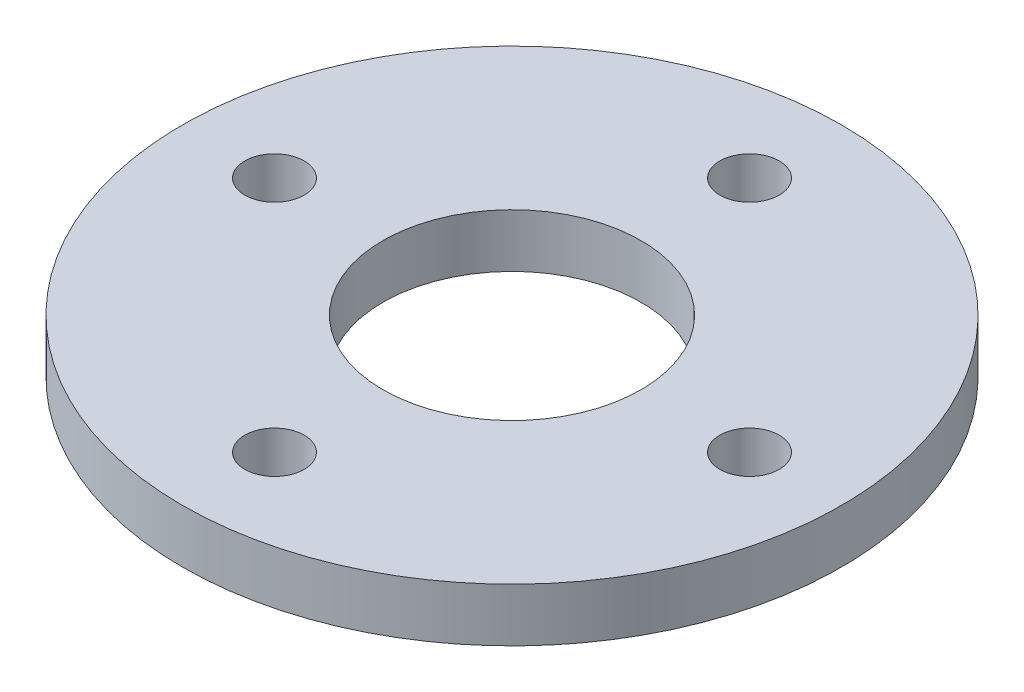
SolidWorks part; units mm, degrees
ref_plane "Alzado" through (0, 0, 0) normal (0, 0, 1) x (1, 0, 0)
ref_plane "Planta" through (0, 0, 0) normal (0, 1, 0) x (1, 0, 0)
ref_plane "Vista lateral" through (0, 0, 0) normal (1, 0, 0) x (0, 0, -1)
sketch "Croquis1" plane through (0, -55.841, 0) normal (0, 1, 0) x (1, 0, 0)
  circle A0 centre (-3.7296, 32.6949) radius 11.1
  circle A1 centre (-11.7296, 32.6949) radius 1
  circle A2 centre (-3.7296, 40.6949) radius 1
  circle A3 centre (4.2704, 32.6949) radius 1
  circle A4 centre (-3.7296, 24.6949) radius 1
  circle A5 centre (-3.7296, 32.6949) radius 4.35
extrude "Saliente-Extruir1" add sketch "Croquis1" along normal blind 1.8
